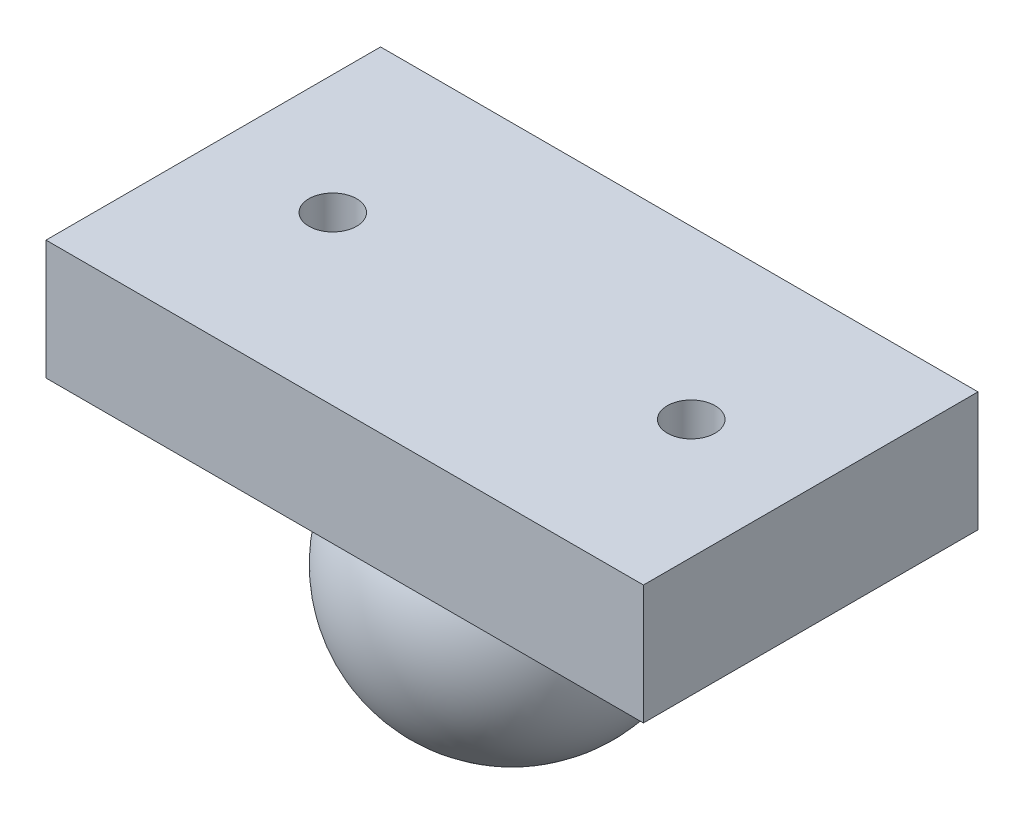
SolidWorks part; units mm, degrees
ref_plane "Front Plane" through (0, 0, 0) normal (0, 0, 1) x (1, 0, 0)
ref_plane "Top Plane" through (0, 0, 0) normal (0, 1, 0) x (1, 0, 0)
ref_plane "Right Plane" through (0, 0, 0) normal (1, 0, 0) x (0, 0, -1)
sketch "Sketch1" plane through (0, 0, 0) normal (0, 1, 0) x (1, 0, 0)
  line L0 (-7.5, 0) -> (7.5, 0) construction
  line L1 (-12.5, 7) -> (12.5, 7)
  line L2 (-12.5, 7) -> (-12.5, -7)
  line L3 (-12.5, -7) -> (12.5, -7)
  line L4 (12.5, 7) -> (12.5, -7)
  line L5 (-12.5, 7) -> (12.5, -7) construction
  line L6 (-12.5, -7) -> (12.5, 7) construction
  circle A0 centre (7.5, 0) radius 1
  circle A1 centre (-7.5, 0) radius 1
  point P0 (0, 0)
  point P9 (0, 0)
  dimension "D4" = 2
  dimension "D1" = 14
  dimension "D2" = 25
  dimension "D3" = 15
extrude "Boss-Extrude1" add sketch "Sketch1" along normal blind 5
sketch "Sketch2" plane through (0, 0, 0) normal (0, 0, 1) x (1, 0, 0)
  line L0 (0, 2) -> (0, -10) construction
  arc A0 (0, -10) -> (0, 2) centre (0, -4) cw
  point P0 (0, -4)
  dimension "D2" = 6
  dimension "D1" = 4
revolve "Revolve-Thin1" add sketch "Sketch2" angle 360 about L0
